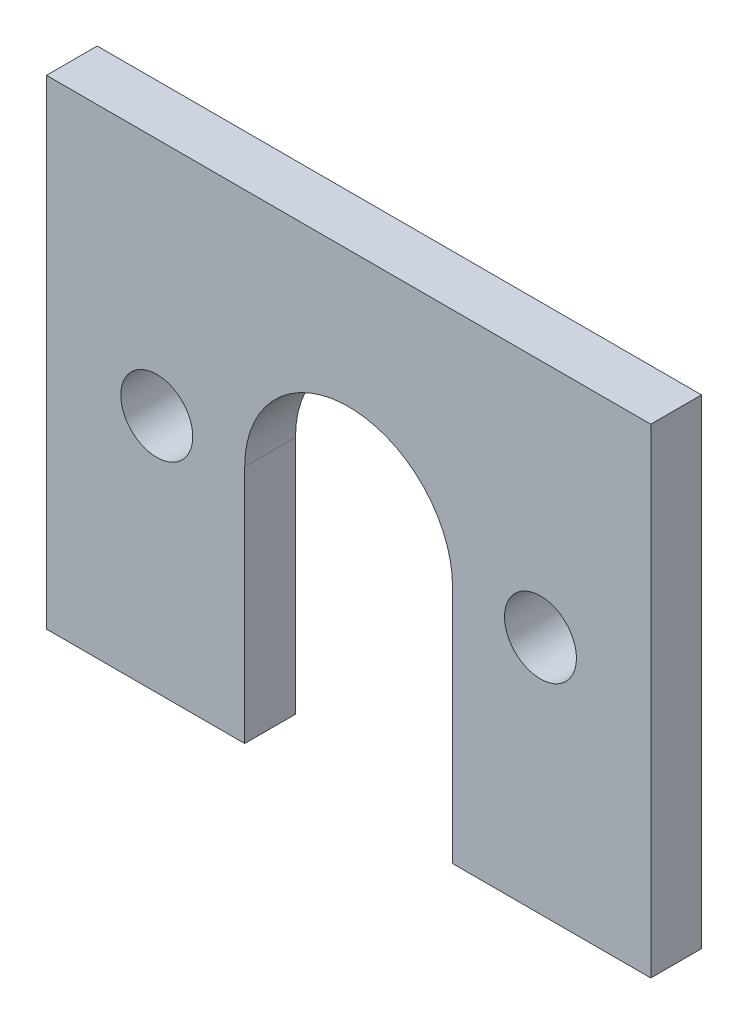
SolidWorks part; units mm, degrees
material "ABS"
ref_plane "X-Y Datum" through (0, 0, 0) normal (0, 0, 1) x (1, 0, 0)
ref_plane "X-Z Datum" through (0, 0, 0) normal (0, 1, 0) x (1, 0, 0)
ref_plane "Y-Z Datum" through (0, 0, 0) normal (1, 0, 0) x (0, 0, -1)
sketch "Sketch1" plane through (0, 0, 0) normal (0, 0, 1) x (1, 0, 0)
  line L1 (-149.85, 38.0375) -> (149.85, 38.0375)
  line L2 (-149.85, 38.0375) -> (-149.85, -38.0375)
  line L3 (-149.85, -38.0375) -> (149.85, -38.0375)
  line L4 (149.85, 38.0375) -> (149.85, -38.0375)
  line L5 (-149.85, 38.0375) -> (149.85, -38.0375) construction
  line L6 (-149.85, -38.0375) -> (149.85, 38.0375) construction
  point P0 (0, 0)
  dimension "D1" = 76.075
  dimension "D2" = 299.7
extrude "Boss-Extrude1" add sketch "Sketch1" along normal blind 3.175
sketch "Sketch3" plane through (0, 0, 0) normal (0, 0, -1) x (-1, 0, 0)
  line L3 (149.85, -38.0375) -> (-149.85, -38.0375) construction
  line L4 (149.85, -38.0375) -> (-149.85, -38.0375)
  line L5 (-104.25, -9.7625) -> (-104.25, -38.0375)
  line L6 (-91.25, -9.7625) -> (-91.25, -38.0375)
  line L7 (104.25, -9.7625) -> (104.25, -38.0375)
  line L8 (91.25, -9.7625) -> (91.25, -38.0375)
  circle A6 centre (-97.75, -9.7625) radius 6.5
  circle A7 centre (97.75, -9.7625) radius 6.5
  point P0 (97.75, -9.7625)
  point P1 (-97.75, -9.7625)
  point P16 (109.75, -9.7625)
  point P17 (85.75, -9.7625)
  point P18 (-85.75, -9.7625)
  point P19 (-109.75, -9.7625)
  dimension "D1" = 13
sketch "Sketch8" plane through (0, 0, 3.175) normal (0, 0, 1) x (1, 0, 0)
  line L0 (128.65, -27.2824) -> (128.65, -38.0375)
  line L1 (121.65, 18.5125) -> (123.65, 18.5125)
  line L3 (-149.85, -38.0375) -> (149.85, -38.0375) construction
  line L4 (122.65, -32.2824) -> (122.65, 18.5125) construction
  line L5 (121.65, -32.2824) -> (123.65, -32.2824)
  line L6 (116.65, -27.2824) -> (116.65, 13.5125)
  line L8 (128.65, -27.2824) -> (128.65, 13.5125)
  line L9 (116.65, -32.2824) -> (128.65, 18.5125) construction
  line L10 (116.65, 18.5125) -> (128.65, -32.2824) construction
  line L12 (116.65, -27.2824) -> (116.65, -38.0375)
  line L13 (-149.85, -38.0375) -> (149.85, -38.0375)
  line L15 (149.85, -38.0375) -> (149.85, 38.0375) construction
  arc A0 (121.65, -32.2824) -> (116.65, -27.2824) centre (121.65, -27.2824) cw
  arc A1 (123.65, -32.2824) -> (128.65, -27.2824) centre (123.65, -27.2824) ccw
  arc A2 (128.65, 13.5125) -> (123.65, 18.5125) centre (123.65, 13.5125) ccw
  arc A3 (121.65, 18.5125) -> (116.65, 13.5125) centre (121.65, 13.5125) ccw
  point P0 (122.65, -6.885)
  line M25 (-149.85, -38.0375) -> (149.85, -38.0375)
  dimension "D1" = 5
  dimension "D2" = 27.2
  dimension "D3" = 31.1525
  dimension "D4" = 12
extrude "Cut-Extrude4" cut sketch "Sketch8" against normal through all contours L1 A3 L6 A0 L5 A1 L8 A2 | A1 L5 A0 L12 L0 M25
mirror "Mirror3" about plane through (0, 0, 0) normal (1, 0, 0) of "Cut-Extrude4"
extrude "Cut-Extrude5" cut sketch "Sketch3" against normal through all contours A6 | A6 L5 L4 L6 | A7 | A7 L8 L4 L7
hole_wizard "M4 Clearance Hole1" positions "Sketch11" profile "Sketch10" hole size "M4" standard "ANSI Metric" end condition through all
sketch "Sketch11" plane through (0, 0, 0) normal (0, 0, -1) x (-1, 0, 0)
  point P0 (-85.75, -9.7625)
  point P3 (-109.75, -9.7625)
  point P6 (109.75, -9.7625)
  point P9 (85.75, -9.7625)
sketch "Sketch10" plane through (85.75, -9.7625, 0) normal (1, 0, 0) x (0, 1, 0)
  line L0 (0, 0) -> (0, 3.175)
  line L1 (0, 3.175) -> (2.25, 3.175)
  line L2 (2.25, 3.175) -> (2.25, 0)
  line L5 (2.25, 0) -> (0, 0)
  line L11 (0, -6.35) -> (0, 107.95) construction
  dimension "Thru Hole Dia." = 4.5
  dimension "Thru Hole Depth" = 3.175
sketch "Sketch12" plane through (0, -38.0375, 0) normal (0, -1, 0) x (1, 0, 0)
  line L0 (0, 0) -> (0, 3.175) construction
  line L1 (-91.25, 0) -> (91.25, 0) construction
  line L2 (-91.25, 3.175) -> (91.25, 3.175) construction
  line L4 (-72, 3.175) -> (72, 3.175)
  line L5 (-72, 3.175) -> (-72, 0)
  line L6 (-72, 0) -> (72, 0)
  line L7 (72, 3.175) -> (72, 0)
  line L8 (-72, 3.175) -> (72, 0) construction
  line L9 (-72, 0) -> (72, 3.175) construction
  point P6 (0, 1.5875)
  dimension "D1" = 144
extrude "Boss-Extrude2" add sketch "Sketch12" along normal blind 6.35
sketch "Sketch13" plane through (0, 0, 0) normal (0, 0, -1) x (-1, 0, 0)
  line L0 (65.2939, -6.6447) -> (60.7239, -6.6447) construction
  line L1 (65.2939, -2.7997) -> (65.2939, -10.4897) construction
  line L2 (60.7239, -10.7897) -> (60.7239, -2.4997) construction
  circle A0 centre (63.0089, -6.6447) radius 14
  dimension "D1" = 28
extrude "Cut-Extrude6" [suppressed] cut sketch "Sketch13" against normal through all
mirror "Mirror4" [suppressed] about plane through (0, 0, 0) normal (1, 0, 0)
sketch "Sketch14" plane through (0, 0, 3.175) normal (0, 0, 1) x (1, 0, 0)
  line L0 (-109.75, -9.7625) -> (-85.75, -9.7625)
  line L1 (-116.65, -38.0375) -> (-116.65, 13.5125) construction
  line L2 (-116.65, 5.2375) -> (-78.85, 5.2375)
  line L3 (-116.65, 5.2375) -> (-116.65, -24.7625)
  line L4 (-116.65, -24.7625) -> (-78.85, -24.7625)
  line L5 (-78.85, 5.2375) -> (-78.85, -24.7625)
  line L6 (-116.65, 5.2375) -> (-78.85, -24.7625) construction
  line L7 (-116.65, -24.7625) -> (-78.85, 5.2375) construction
  line L30 (-91.25, -38.0375) -> (-72, -38.0375)
  line L31 (-72, -38.0375) -> (-72, -44.3875)
  line L32 (-72, -44.3875) -> (72, -44.3875)
  line L33 (72, -44.3875) -> (72, -38.0375)
  line L34 (72, -38.0375) -> (91.25, -38.0375)
  line L35 (91.25, -38.0375) -> (91.25, -9.7625)
  line L36 (104.25, -9.7625) -> (104.25, -38.0375)
  line L37 (104.25, -38.0375) -> (116.65, -38.0375)
  line L38 (116.65, -38.0375) -> (116.65, 13.5125)
  line L39 (121.65, 18.5125) -> (123.65, 18.5125)
  line L40 (128.65, 13.5125) -> (128.65, -38.0375)
  line L41 (128.65, -38.0375) -> (149.85, -38.0375)
  line L42 (149.85, -38.0375) -> (149.85, 38.0375)
  line L43 (149.85, 38.0375) -> (-149.85, 38.0375)
  line L44 (-149.85, 38.0375) -> (-149.85, -38.0375)
  line L45 (-149.85, -38.0375) -> (-128.65, -38.0375)
  line L46 (-128.65, -38.0375) -> (-128.65, 13.5125)
  line L47 (-123.65, 18.5125) -> (-121.65, 18.5125)
  line L48 (-116.65, 13.5125) -> (-116.65, -38.0375)
  line L49 (-116.65, -38.0375) -> (-104.25, -38.0375)
  line L50 (-104.25, -38.0375) -> (-104.25, -9.7625)
  line L51 (-91.25, -9.7625) -> (-91.25, -38.0375)
  line L52 (-91.25, -38.0375) -> (-72, -38.0375)
  line L53 (-72, -38.0375) -> (-72, -44.3875)
  line L54 (-72, -44.3875) -> (72, -44.3875)
  line L55 (72, -44.3875) -> (72, -38.0375)
  line L56 (72, -38.0375) -> (91.25, -38.0375)
  line L57 (91.25, -38.0375) -> (91.25, -9.7625)
  line L58 (104.25, -9.7625) -> (104.25, -38.0375)
  line L59 (104.25, -38.0375) -> (116.65, -38.0375)
  line L60 (116.65, -38.0375) -> (116.65, 13.5125)
  line L61 (121.65, 18.5125) -> (123.65, 18.5125)
  line L62 (128.65, 13.5125) -> (128.65, -38.0375)
  line L63 (128.65, -38.0375) -> (149.85, -38.0375)
  line L64 (149.85, -38.0375) -> (149.85, 38.0375)
  line L65 (149.85, 38.0375) -> (-149.85, 38.0375)
  line L66 (-149.85, 38.0375) -> (-149.85, -38.0375)
  line L67 (-149.85, -38.0375) -> (-128.65, -38.0375)
  line L68 (-128.65, -38.0375) -> (-128.65, 13.5125)
  line L69 (-123.65, 18.5125) -> (-121.65, 18.5125)
  line L70 (-116.65, 13.5125) -> (-116.65, -38.0375)
  line L71 (-116.65, -38.0375) -> (-104.25, -38.0375)
  line L72 (-104.25, -38.0375) -> (-104.25, -9.7625)
  line L73 (-91.25, -9.7625) -> (-91.25, -38.0375)
  arc A6 (104.25, -9.7625) -> (91.25, -9.7625) centre (97.75, -9.7625) ccw
  arc A7 (121.65, 18.5125) -> (116.65, 13.5125) centre (121.65, 13.5125) ccw
  arc A8 (128.65, 13.5125) -> (123.65, 18.5125) centre (123.65, 13.5125) ccw
  arc A9 (-123.65, 18.5125) -> (-128.65, 13.5125) centre (-123.65, 13.5125) ccw
  arc A10 (-116.65, 13.5125) -> (-121.65, 18.5125) centre (-121.65, 13.5125) ccw
  arc A11 (-91.25, -9.7625) -> (-104.25, -9.7625) centre (-97.75, -9.7625) ccw
  arc A12 (104.25, -9.7625) -> (91.25, -9.7625) centre (97.75, -9.7625) ccw
  arc A13 (121.65, 18.5125) -> (116.65, 13.5125) centre (121.65, 13.5125) ccw
  arc A14 (128.65, 13.5125) -> (123.65, 18.5125) centre (123.65, 13.5125) ccw
  arc A15 (-123.65, 18.5125) -> (-128.65, 13.5125) centre (-123.65, 13.5125) ccw
  arc A16 (-116.65, 13.5125) -> (-121.65, 18.5125) centre (-121.65, 13.5125) ccw
  arc A17 (-91.25, -9.7625) -> (-104.25, -9.7625) centre (-97.75, -9.7625) ccw
  point P4 (-97.75, -9.7625)
  circle M31 centre (109.75, -9.7625) radius 2.25
  line M32 (-91.25, -38.0375) -> (-72, -38.0375)
  line M33 (-72, -38.0375) -> (-72, -44.3875)
  line M34 (-72, -44.3875) -> (72, -44.3875)
  line M35 (72, -44.3875) -> (72, -38.0375)
  line M36 (72, -38.0375) -> (91.25, -38.0375)
  line M37 (91.25, -38.0375) -> (91.25, -9.7625)
  arc M38 (91.25, -9.7625) -> (104.25, -9.7625) centre (97.75, -9.7625) cw
  line M39 (104.25, -9.7625) -> (104.25, -38.0375)
  line M40 (104.25, -38.0375) -> (116.65, -38.0375)
  line M41 (116.65, -38.0375) -> (116.65, 13.5125)
  arc M42 (116.65, 13.5125) -> (121.65, 18.5125) centre (121.65, 13.5125) cw
  line M43 (121.65, 18.5125) -> (123.65, 18.5125)
  arc M44 (123.65, 18.5125) -> (128.65, 13.5125) centre (123.65, 13.5125) cw
  line M45 (128.65, 13.5125) -> (128.65, -38.0375)
  line M46 (128.65, -38.0375) -> (149.85, -38.0375)
  line M47 (149.85, -38.0375) -> (149.85, 38.0375)
  line M48 (149.85, 38.0375) -> (-149.85, 38.0375)
  line M49 (-149.85, 38.0375) -> (-149.85, -38.0375)
  line M50 (-149.85, -38.0375) -> (-128.65, -38.0375)
  line M51 (-128.65, -38.0375) -> (-128.65, 13.5125)
  arc M52 (-128.65, 13.5125) -> (-123.65, 18.5125) centre (-123.65, 13.5125) cw
  line M53 (-123.65, 18.5125) -> (-121.65, 18.5125)
  arc M54 (-121.65, 18.5125) -> (-116.65, 13.5125) centre (-121.65, 13.5125) cw
  line M55 (-116.65, 13.5125) -> (-116.65, -38.0375)
  line M56 (-116.65, -38.0375) -> (-104.25, -38.0375)
  line M57 (-104.25, -38.0375) -> (-104.25, -9.7625)
  line M59 (-91.25, -9.7625) -> (-91.25, -38.0375)
  circle M62 centre (85.75, -9.7625) radius 2.25
  dimension "D1" = 30
  dimension "D2" = 0
extrude "Cut-Extrude7" cut sketch "Sketch14" against normal through all contours L2 L5 L4 M59 M32 M33 M34 M35 M36 M37 M38 M39 M40 M41 M42 M43 M44 M45 M46 M47 M48 M49 M50 M51 M52 M53 M54 M55 M62 M31 | L4 M55 M56 M57
